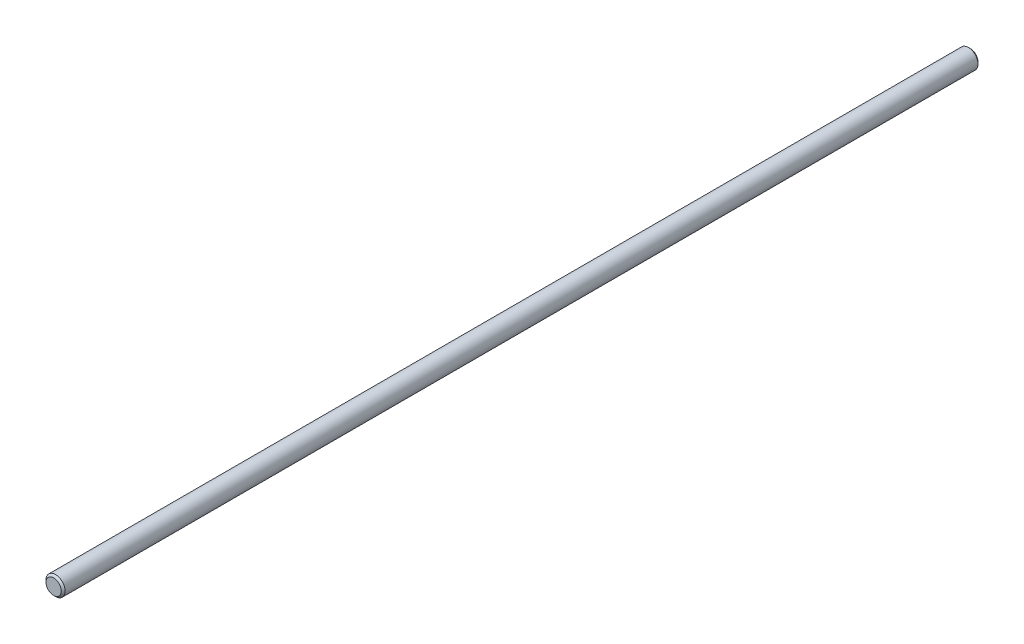
SolidWorks part; units mm, degrees
material "Plain Carbon Steel"
ref_plane "Front" through (0, 0, 0) normal (0, 0, 1) x (1, 0, 0)
ref_plane "Top" through (0, 0, 0) normal (0, 1, 0) x (1, 0, 0)
ref_plane "Right" through (0, 0, 0) normal (1, 0, 0) x (0, 0, -1)
sketch "Sketch1" plane through (0, 0, 0) normal (0, 0, 1) x (1, 0, 0)
  circle A0 centre (0, 0) radius 3.175
  dimension "dia" = 6.35
sketch "Sketch3" plane through (0, 0, 0) normal (0, 0, 1) x (1, 0, 0)
  circle A0 centre (0, 0) radius 3.175 construction
  circle A1 centre (0, 0) radius 3.175
extrude "Boss-Extrude1" add sketch "Sketch3" along normal mid plane 304.8
sketch "Sketch2" plane through (0, 0, 0) normal (1, 0, 0) x (0, 0, -1)
  line L0 (152.4, 3.175) -> (-152.4, 3.175) construction
  point P0 (-152.4, 3.175)
  point P1 (152.4, 3.175)
  point P2 (-139.7, 3.175)
  point P3 (139.7, 3.175)
  dimension "D1" = 12.7
  dimension "D2" = 12.7
chamfer "Chamfer1" distance 0.635 angle 45 2 edges at (3.175, 0, 152.4) (3.175, 0, -152.4)
equation "\"D1@Chamfer1\" = \"dia@Sketch1\" / 10"
equation "\"D1@Sketch2\"=\"dia@Sketch1\"*2"
equation "\"D2@Sketch2\"=\"D1@Sketch2\""
